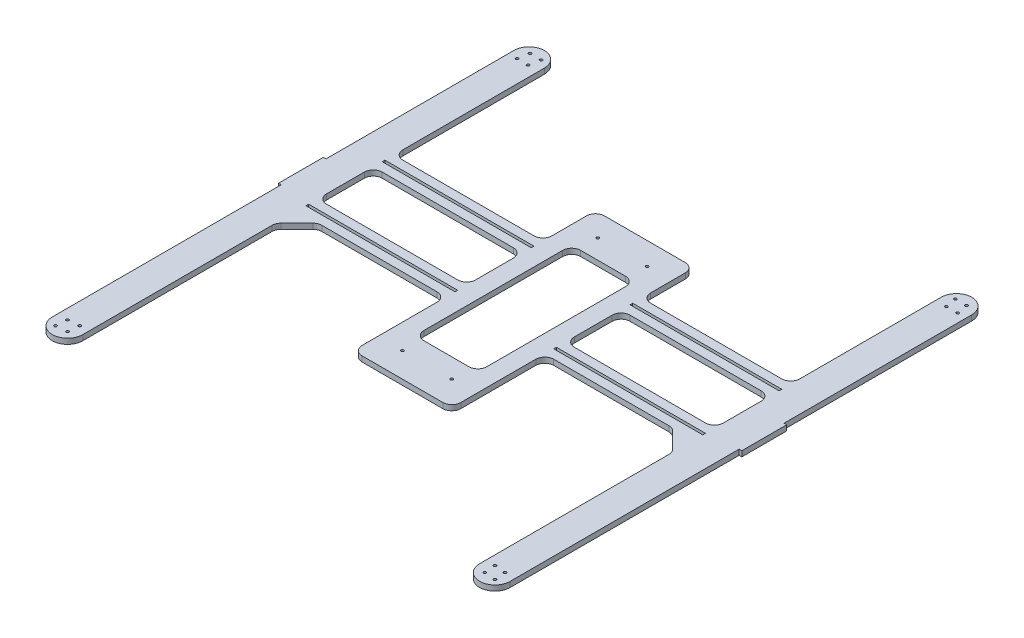
SolidWorks part; units mm, degrees
ref_plane "Front Plane" through (0, 0, 0) normal (0, 0, 1) x (1, 0, 0)
ref_plane "Top Plane" through (0, 0, 0) normal (0, 1, 0) x (1, 0, 0)
ref_plane "Right Plane" through (0, 0, 0) normal (1, 0, 0) x (0, 0, -1)
sketch "Sketch1" plane through (0, 0, 0) normal (0, 1, 0) x (1, 0, 0)
  line L1 (216, -40) -> (216, -255)
  line L4 (216, 78.5) -> (216, 81.5)
  line L5 (250, -255) -> (250, 0)
  line L6 (50, -120) -> (250, -120) construction
  line L7 (50, 150) -> (50, 91.5) construction
  line L8 (50, 150) -> (250, 120) construction
  line L10 (227.9078, 252.8902) -> (238.0922, 265.2304) construction
  line L11 (240.327, 253.0134) -> (225.673, 265.1073) construction
  line L12 (227.3431, -260.6569) -> (238.6569, -249.3431) construction
  line L13 (0, 25) -> (250, 25) construction
  line L14 (226.2825, -248.2825) -> (239.7175, -261.7175) construction
  line L18 (250, 0) -> (253, 0)
  line L19 (253, 0) -> (253, 50)
  line L20 (253, 50) -> (250, 50)
  line L21 (250, 50) -> (250, 259.0603)
  line L22 (50, 81.5) -> (50, 78.5) construction
  line L23 (50, 81.5) -> (50, 78.5)
  line L24 (50, -3.5) -> (50, -6.5) construction
  line L25 (50, -16.5) -> (50, -120) construction
  line L26 (50, 68.5) -> (50, 6.5)
  line L27 (-60, -5) -> (-226, -5) construction
  line L28 (216, 68.5) -> (216, 6.5)
  line L29 (-226, 68.5) -> (-226, 6.5)
  line L47 (-5, 150) -> (-5, -120) construction
  line L48 (-60, -120) -> (50, -120)
  line L53 (-60, 150) -> (50, 150)
  line L54 (50, 150) -> (50, 91.5)
  line L57 (250, -120) -> (250, -5) construction
  line L58 (50, -3.5) -> (50, -6.5)
  line L59 (216, -6.5) -> (50, -6.5)
  line L60 (50, 80) -> (216, 80) construction
  line L61 (250, 80) -> (250, 81.5) construction
  line L62 (216, 81.5) -> (50, 81.5)
  line L63 (216, -3.5) -> (50, -3.5)
  line L64 (250, 80) -> (250, 78.5) construction
  line L65 (216, 78.5) -> (50, 78.5)
  line L66 (-60, 80) -> (-226, 80) construction
  line L67 (50, 91.5) -> (216, 91.5)
  line L68 (-260, -120) -> (-260, -5) construction
  line L69 (50, 68.5) -> (216, 68.5)
  line L70 (50, -120) -> (50, -16.5)
  line L71 (-60, -16.5) -> (-60, -120) construction
  line L72 (50, -16.5) -> (192.5, -16.5)
  line L73 (-60, -3.5) -> (-60, -6.5) construction
  line L74 (50, 6.5) -> (216, 6.5)
  line L75 (192.5, -16.5) -> (216, -40)
  line L76 (50, -5) -> (216, -5) construction
  line L79 (216, -6.5) -> (216, -3.5)
  line L80 (216, 91.5) -> (216, 259.0603)
  line L81 (-60, 81.5) -> (-60, 78.5) construction
  line L82 (-236.2825, -248.2825) -> (-249.7175, -261.7175) construction
  line L83 (-10, 25) -> (-260, 25) construction
  line L84 (-237.3431, -260.6569) -> (-248.6569, -249.3431) construction
  line L85 (-250.327, 253.0134) -> (-235.673, 265.1073) construction
  line L86 (-237.9078, 252.8902) -> (-248.0922, 265.2304) construction
  line L87 (-60, 150) -> (-260, 120) construction
  line L88 (-60, 150) -> (-60, 91.5) construction
  line L89 (-60, -120) -> (-260, -120) construction
  line L90 (-226, 91.5) -> (-226, 259.0603)
  line L91 (-226, -6.5) -> (-226, -3.5)
  line L93 (-202.5, -16.5) -> (-226, -40)
  line L94 (-60, 6.5) -> (-226, 6.5)
  line L95 (-60, -16.5) -> (-202.5, -16.5)
  line L96 (-60, -120) -> (-60, -16.5)
  line L97 (-60, 68.5) -> (-226, 68.5)
  line L98 (-60, 91.5) -> (-226, 91.5)
  line L99 (-226, 78.5) -> (-60, 78.5)
  line L100 (-226, -3.5) -> (-60, -3.5)
  line L101 (-226, 81.5) -> (-60, 81.5)
  line L102 (-226, -6.5) -> (-60, -6.5)
  line L103 (-60, -3.5) -> (-60, -6.5)
  line L104 (-60, 150) -> (-60, 91.5)
  line L105 (-60, 68.5) -> (-60, 6.5)
  line L106 (-60, 81.5) -> (-60, 78.5)
  line L107 (-260, 50) -> (-260, 259.0603)
  line L108 (-263, 50) -> (-260, 50)
  line L109 (-263, 0) -> (-263, 50)
  line L110 (-260, 0) -> (-263, 0)
  line L111 (-260, -255) -> (-260, 0)
  line L112 (-226, 78.5) -> (-226, 81.5)
  line L113 (-226, -40) -> (-226, -255)
  line L121 (30, 103.5) -> (30, -71)
  line L122 (30, 103.5) -> (-40, 103.5)
  line L123 (-40, 103.5) -> (-40, -71)
  line L124 (-40, -71) -> (30, -71)
  arc A0 (216, -255) -> (250, -255) centre (233, -255) ccw
  arc A1 (216, 259.0603) -> (250, 259.0603) centre (233, 259.0603) cw
  circle A2 centre (233, -255) radius 135 construction
  circle A3 centre (233, 259.0603) radius 135 construction
  circle A4 centre (238.0922, 265.2304) radius 1.5
  circle A5 centre (225.673, 265.1073) radius 1.5
  circle A6 centre (227.9078, 252.8902) radius 1.5
  circle A7 centre (240.327, 253.0134) radius 1.5
  circle A8 centre (226.2825, -248.2825) radius 1.5
  circle A9 centre (238.6569, -249.3431) radius 1.5
  circle A10 centre (239.7175, -261.7175) radius 1.5
  circle A11 centre (227.3431, -260.6569) radius 1.5
  circle A33 centre (22.5, 125) radius 1.5
  circle A36 centre (-243, 259.0603) radius 135 construction
  circle A37 centre (-243, -255) radius 135 construction
  circle A39 centre (-32.5, 125) radius 1.5
  circle A40 centre (-237.3431, -260.6569) radius 1.5
  circle A41 centre (-249.7175, -261.7175) radius 1.5
  circle A42 centre (-248.6569, -249.3431) radius 1.5
  circle A43 centre (-236.2825, -248.2825) radius 1.5
  circle A44 centre (-250.327, 253.0134) radius 1.5
  circle A45 centre (-237.9078, 252.8902) radius 1.5
  circle A46 centre (-235.673, 265.1073) radius 1.5
  circle A47 centre (-248.0922, 265.2304) radius 1.5
  arc A48 (-226, 259.0603) -> (-260, 259.0603) centre (-243, 259.0603) ccw
  arc A49 (-226, -255) -> (-260, -255) centre (-243, -255) cw
  circle A50 centre (22.5, -92.5) radius 1.5
  circle A51 centre (-32.5, -92.5) radius 1.5
  point P12 (250, 120)
  point P13 (250, -120)
  point P15 (50, -120)
  point P134 (-60, -120)
  point P135 (-260, -120)
  point P136 (-260, 120)
  dimension "D1" = 17
  dimension "D3" = 270
  dimension "D4" = 270
  dimension "D12" = 3
  dimension "D13" = 3
  dimension "D14" = 3
  dimension "D15" = 3
  dimension "D20" = 3
  dimension "D21" = 3
  dimension "D22" = 3
  dimension "D23" = 3
  dimension "D5" = 240
  dimension "D6" = 200
  dimension "D9" = 16
  dimension "D10" = 19
  dimension "D16" = 270
  dimension "D17" = 45
  dimension "D18" = 16
  dimension "D19" = 19
extrude "Boss-Extrude1" add sketch "Sketch1" along normal blind 6
fillet "Скругление1" radius 10 26 edges at (216, 3, -6.5) (216, 3, -68.5) (216, 3, -91.5) (-226, 3, -6.5) (-226, 3, -68.5) (-226, 3, -91.5) (-226, 3, 40) (-202.5, 3, 16.5) (216, 3, 40) (192.5, 3, 16.5) (-40, 3, 71) (30, 3, 71) (30, 3, -103.5) (-40, 3, -103.5) (-60, 3, -150) (50, 3, -150) (-60, 3, 120) (50, 3, 120) (50, 3, -68.5) (50, 3, -91.5) (50, 3, -6.5) (50, 3, 16.5) (-60, 3, -91.5) (-60, 3, 16.5) (-60, 3, -6.5) (-60, 3, -68.5)
